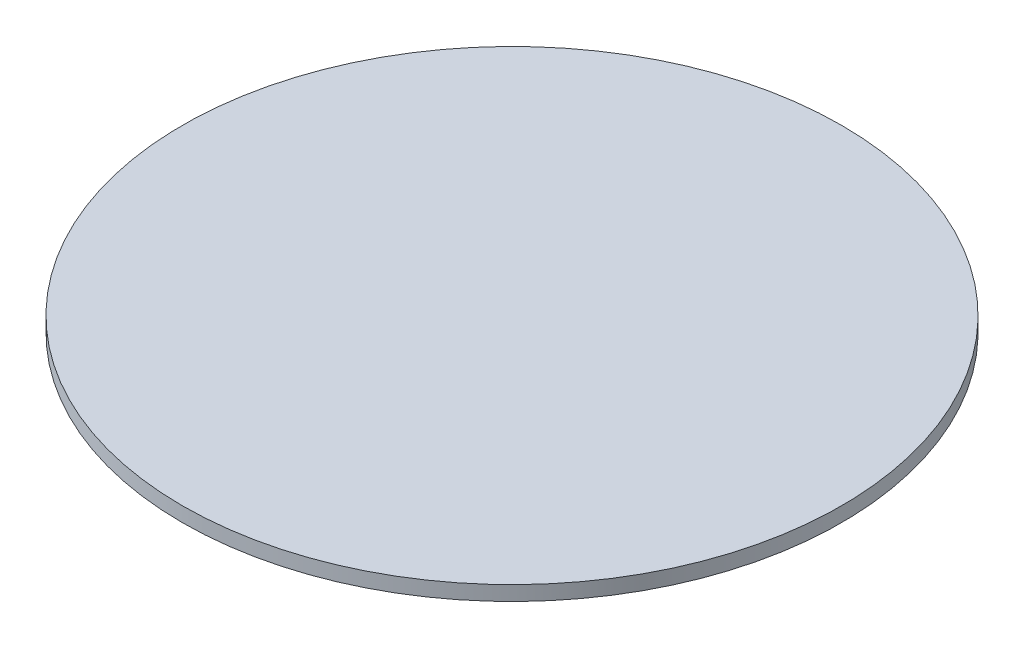
SolidWorks part; units mm, degrees
ref_plane "前基準面" through (0, 0, 0) normal (0, 0, 1) x (1, 0, 0)
ref_plane "上基準面" through (0, 0, 0) normal (0, 1, 0) x (1, 0, 0)
ref_plane "右基準面" through (0, 0, 0) normal (1, 0, 0) x (0, 0, -1)
sketch "草圖1" plane through (0, 0, 0) normal (0, 1, 0) x (1, 0, 0)
  circle A0 centre (0, 0) radius 90
extrude "填料-伸長1" add sketch "草圖1" along normal blind 4
